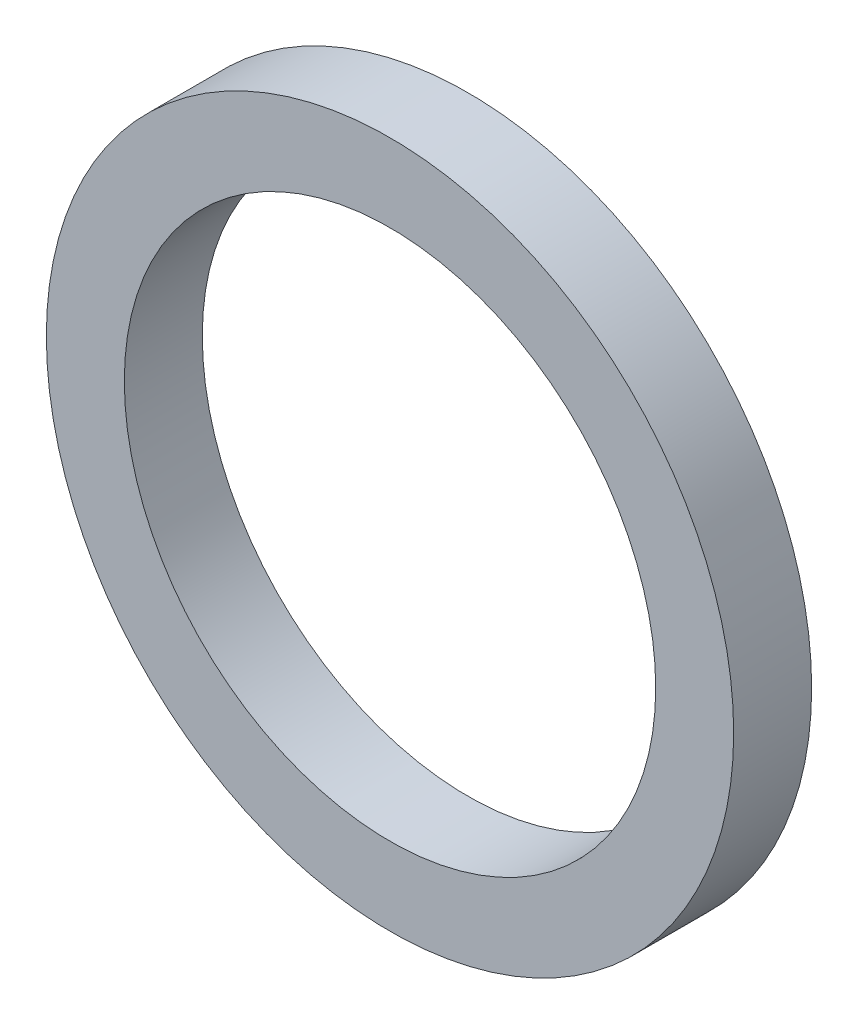
SolidWorks part; units mm, degrees
ref_plane "Front" through (0, 0, 0) normal (0, 0, 1) x (1, 0, 0)
ref_plane "Top" through (0, 0, 0) normal (0, 1, 0) x (1, 0, 0)
ref_plane "Right" through (0, 0, 0) normal (1, 0, 0) x (0, 0, -1)
sketch "Sketch1" plane through (0, 0, 0) normal (0, 1, 0) x (1, 0, 0)
  line L0 (0, -0.635) -> (0, 0.635) construction
  line L1 (0, -0.8731) -> (0, 0.8731) construction
  line L3 (-5.4102, 0) -> (5.4102, 0) construction
  line L4 (5.4102, -0.9525) -> (5.4102, 0.635)
  line L5 (5.4102, -0.9525) -> (6.9977, -0.9525)
  line L6 (5.4102, 0.635) -> (6.9977, 0.635)
  line L7 (6.9977, -0.9525) -> (6.9977, 0.635)
  point P9 (5.4102, 0)
  point P10 (1.8034, 0)
  point P13 (1.1684, 0.635)
  point P14 (1.1684, -0.635)
  dimension "D1" = 1.5875
  dimension "Width" = 1.5875
  dimension "ID" = 10.8204
revolve "Revolve1" add sketch "Sketch1" angle 360 about L0
sketch "Sketch3" plane through (0, 0, 0) normal (1, 0, 0) x (0, 0, -1)
  line L0 (-0.7937, 0) -> (0.7937, 0) construction
  point P6 (0, 0)
  point P7 (0, 0)
  dimension "D1" = 1.5875
sketch "Sketch4" plane through (0, 0, 0) normal (0, 0, 1) x (1, 0, 0)
  line L1 (0, 0) -> (-6.8396, 1.479) construction
  circle A0 centre (0, 0) radius 6.9977 construction
equation "\"D1@Sketch3\" = \"Width@Sketch1\""
equation "\"D1@Sketch1\" = \"Width@Sketch1\""
